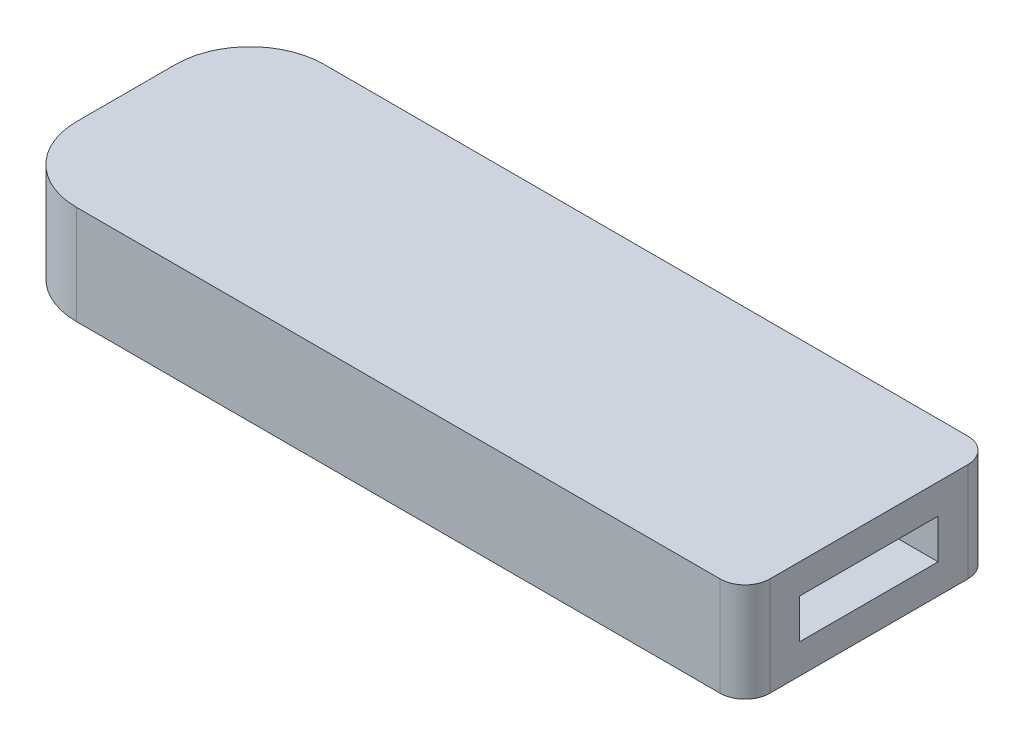
SolidWorks part; units mm, degrees
ref_plane "Front Plane" through (0, 0, 0) normal (0, 0, 1) x (1, 0, 0)
ref_plane "Top Plane" through (0, 0, 0) normal (0, 1, 0) x (1, 0, 0)
ref_plane "Right Plane" through (0, 0, 0) normal (1, 0, 0) x (0, 0, -1)
sketch "Sketch1" plane through (0, 0, 0) normal (0, 1, 0) x (1, 0, 0)
  line L1 (0, 0) -> (-30, 0)
  line L2 (0, 0) -> (0, 10)
  line L3 (0, 10) -> (-30, 10)
  line L4 (-30, 0) -> (-30, 10)
  dimension "D1" = 30
  dimension "D2" = 10
extrude "Boss-Extrude1" add sketch "Sketch1" along normal blind 4
sketch "Sketch2" plane through (0, 0, 0) normal (1, 0, 0) x (0, 0, -1)
  line L1 (2.2, 2.8) -> (7.8, 2.8)
  line L2 (2.2, 2.8) -> (2.2, 1.2)
  line L3 (2.2, 1.2) -> (7.8, 1.2)
  line L4 (7.8, 2.8) -> (7.8, 1.2)
  line L5 (0, 4) -> (10, 4) construction
  line L6 (10, 4) -> (10, 0) construction
  point P4 (5, 4)
  point P7 (5, 2.8)
  point P10 (10, 2)
  point P11 (7.8, 2)
  dimension "D1" = 1.6
  dimension "D2" = 5.6
extrude "Cut-Extrude1" cut sketch "Sketch2" against normal blind 13
fillet "Fillet1" radius 3 2 edges at (-30, 2, 0) (-30, 2, -10)
fillet "Fillet2" radius 1 2 edges at (0, 2, 0) (0, 2, -10)
